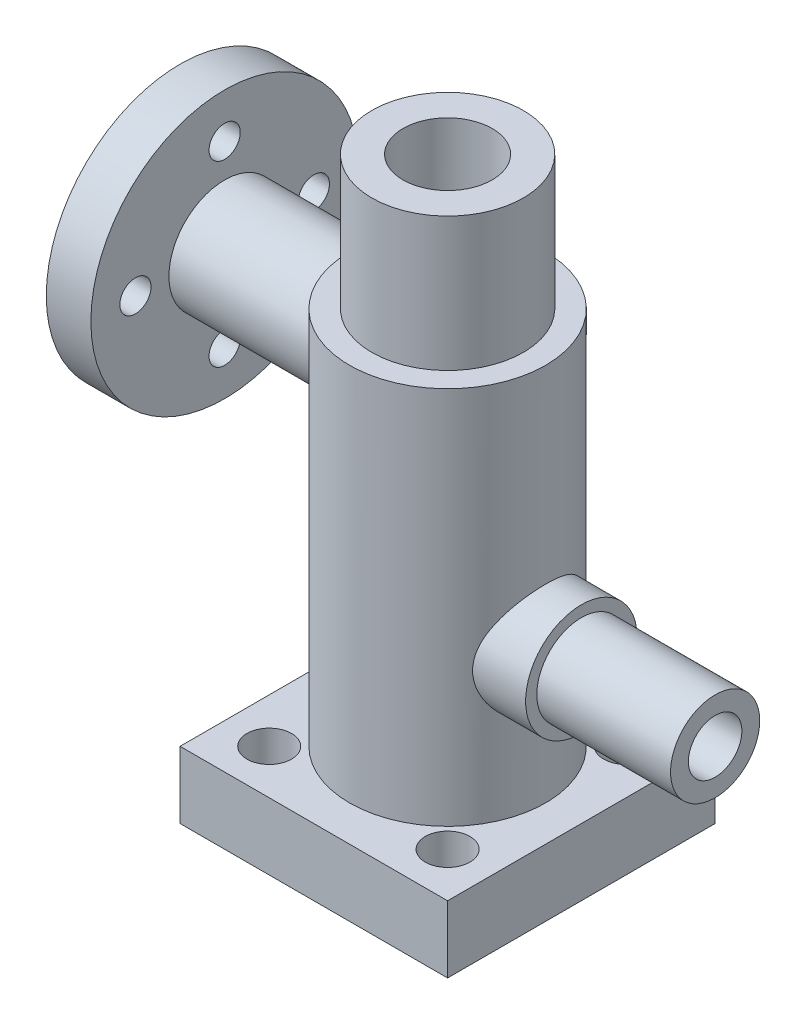
SolidWorks part; units mm, degrees
ref_plane "Front Plane" through (0, 0, 0) normal (0, 0, 1) x (1, 0, 0)
ref_plane "Top Plane" through (0, 0, 0) normal (0, 1, 0) x (1, 0, 0)
ref_plane "Right Plane" through (0, 0, 0) normal (1, 0, 0) x (0, 0, -1)
sketch "Sketch1" plane through (0, 0, 0) normal (0, 1, 0) x (1, 0, 0)
  line L1 (-30, 30) -> (30, 30)
  line L2 (-30, 30) -> (-30, -30)
  line L3 (-30, -30) -> (30, -30)
  line L4 (30, 30) -> (30, -30)
  line L5 (-30, 30) -> (30, -30) construction
  line L6 (-30, -30) -> (30, 30) construction
  point P0 (0, 0)
  dimension "D1" = 60
  dimension "D2" = 60
extrude "Boss-Extrude1" add sketch "Sketch1" along normal blind 15
sketch "Sketch2" plane through (0, 15, 0) normal (0, 1, 0) x (1, 0, 0)
  circle A0 centre (0, 0) radius 22
  dimension "D1" = 44
extrude "Boss-Extrude2" add sketch "Sketch2" along normal blind 85
sketch "Sketch3" plane through (0, 100, 0) normal (0, 1, 0) x (1, 0, 0)
  circle A0 centre (0, 0) radius 17
  dimension "D1" = 34
extrude "Boss-Extrude3" add sketch "Sketch3" along normal blind 30
hole_wizard "Hole1" positions "Sketch5" profile "Sketch6" legacy
sketch "Sketch5" plane through (0, 130, 0) normal (0, 1, 0) x (1, 0, 0)
  point P0 (0, 0)
sketch "Sketch6" plane through (0, 130, 0) normal (1, 0, 0) x (0, 0, 1)
  line L0 (0, 0) -> (0, 115)
  line L1 (0, 115) -> (10, 115)
  line L2 (10, 115) -> (10, 0)
  line L3 (10, 0) -> (0, 0)
  line L4 (0, 110) -> (0, -10) construction
  dimension "Diameter" = 20
  dimension "Depth" = 115
sketch "Sketch9" plane through (0, 15, 0) normal (0, 1, 0) x (1, 0, 0)
  line L0 (30, -30) -> (30, 30) construction
  line L1 (30, 30) -> (-30, 30) construction
  circle A0 centre (20, 20) radius 5
  dimension "D1" = 10
  dimension "D2" = 10
  dimension "D3" = 10
extrude "Cut-Extrude1" cut sketch "Sketch9" against normal through all
mirror "Mirror1" about plane through (0, 0, 0) normal (1, 0, 0) of "Cut-Extrude1"
mirror "Mirror2" about plane through (0, 0, 0) normal (0, 0, 1) of "Mirror1", "Cut-Extrude1"
ref_plane "Plane1" through (-60, 0, 0) normal (1, 0, 0) x (0, 0, -1)
sketch "Sketch10" plane through (-60, 0, 0) normal (1, 0, 0) x (0, 0, -1)
  line L0 (17, 130) -> (-17, 130) construction
  circle A0 centre (0, 87.5) radius 12.5
  dimension "D1" = 25
  dimension "D2" = 42.5
extrude "Boss-Extrude4" add sketch "Sketch10" along normal up to next
sketch "Sketch11" plane through (-60, 0, 0) normal (-1, 0, 0) x (0, 0, 1)
  circle A0 centre (0, 87.5) radius 30
  dimension "D1" = 60
extrude "Boss-Extrude5" add sketch "Sketch11" against normal blind 10
hole_wizard "Hole2" positions "Sketch12" profile "Sketch13" legacy
sketch "Sketch12" plane through (-60, 0, 0) normal (-1, 0, 0) x (0, 0, 1)
  point P0 (0, 87.5)
sketch "Sketch13" plane through (-60, 87.5, 0) normal (0, 1, 0) x (0, 0, 1)
  line L0 (0, 0) -> (0, 50)
  line L1 (0, 50) -> (10, 50)
  line L2 (10, 50) -> (10, 0)
  line L3 (10, 0) -> (0, 0)
  line L4 (0, 110) -> (0, -10) construction
  dimension "Diameter" = 20
  dimension "Depth" = 50
hole_wizard "Tap Drill for M8x1.0 Tap1" positions "Sketch16" profile "Sketch15" hole size "M8x1.0" standard "ISO"
sketch "Sketch16" plane through (-60, 0, 0) normal (-1, 0, 0) x (0, 0, 1)
  line L0 (0, 87.5) -> (20, 87.5) construction
  point P0 (20, 87.5)
  point P9 (19.4094, 87.5)
  dimension "D1" = 20
sketch "Sketch15" plane through (-60, 87.5, 20) normal (0, 1, 0) x (0, 0, 1)
  line L0 (0, 0) -> (0, 10)
  line L1 (0, 10) -> (3.5, 10)
  line L2 (3.5, 10) -> (3.5, 0.025)
  line L3 (3.5, 0.025) -> (3.525, 0)
  line L5 (3.525, 0) -> (0, 0)
  line L6 (-3.5, 0.025) -> (-3.525, 0) construction
  line L11 (0, -6.35) -> (0, 107.95) construction
  dimension "Thru Hole Dia." = 7
  dimension "Thru Hole Depth" = 10
  dimension "Near C'Sink Dia." = 7.05
  dimension "Near C'Sink Angle" = 90
pattern_circular "CirPattern1" count 4 over 360 about axis through (0, 87.5, 0) along (1, 0, 0) of "Tap Drill for M8x1.0 Tap1"
ref_plane "Plane2" through (60, 0, 0) normal (1, 0, 0) x (0, 0, -1)
sketch "Sketch18" plane through (60, 0, 0) normal (1, 0, 0) x (0, 0, -1)
  circle A0 centre (0, 45) radius 12.5
  point P2 (-153.4439, 95.5789)
  point P4 (0, 45)
  dimension "D1" = 25
  dimension "D2" = 45
extrude "Boss-Extrude6" add sketch "Sketch18" against normal up to next from offset 30 offset against normal yes
sketch "Sketch19" plane through (30, 0, 0) normal (1, 0, 0) x (0, 0, -1)
  circle A0 centre (0, 45) radius 10
  circle A1 centre (0, 45) radius 12.5 construction
  circle A2 centre (0, 45) radius 12.5
  dimension "D1" = 20
sketch "Sketch20" plane through (30, 0, 0) normal (1, 0, 0) x (0, 0, -1)
  circle A0 centre (0, 45) radius 10
  dimension "D1" = 20
extrude "Boss-Extrude7" add sketch "Sketch20" along normal up to surface (30 mm away) up to plane "Plane2"
hole_wizard "Hole3" positions "Sketch21" profile "Sketch22" legacy
sketch "Sketch21" plane through (60, 0, 0) normal (1, 0, 0) x (0, 0, -1)
  point P0 (0, 45)
sketch "Sketch22" plane through (60, 45, 0) normal (0, 1, 0) x (0, 0, -1)
  line L0 (0, 0) -> (0, 50)
  line L1 (0, 50) -> (6, 50)
  line L2 (6, 50) -> (6, 0)
  line L3 (6, 0) -> (0, 0)
  line L4 (0, 110) -> (0, -10) construction
  dimension "Diameter" = 12
  dimension "Depth" = 50
